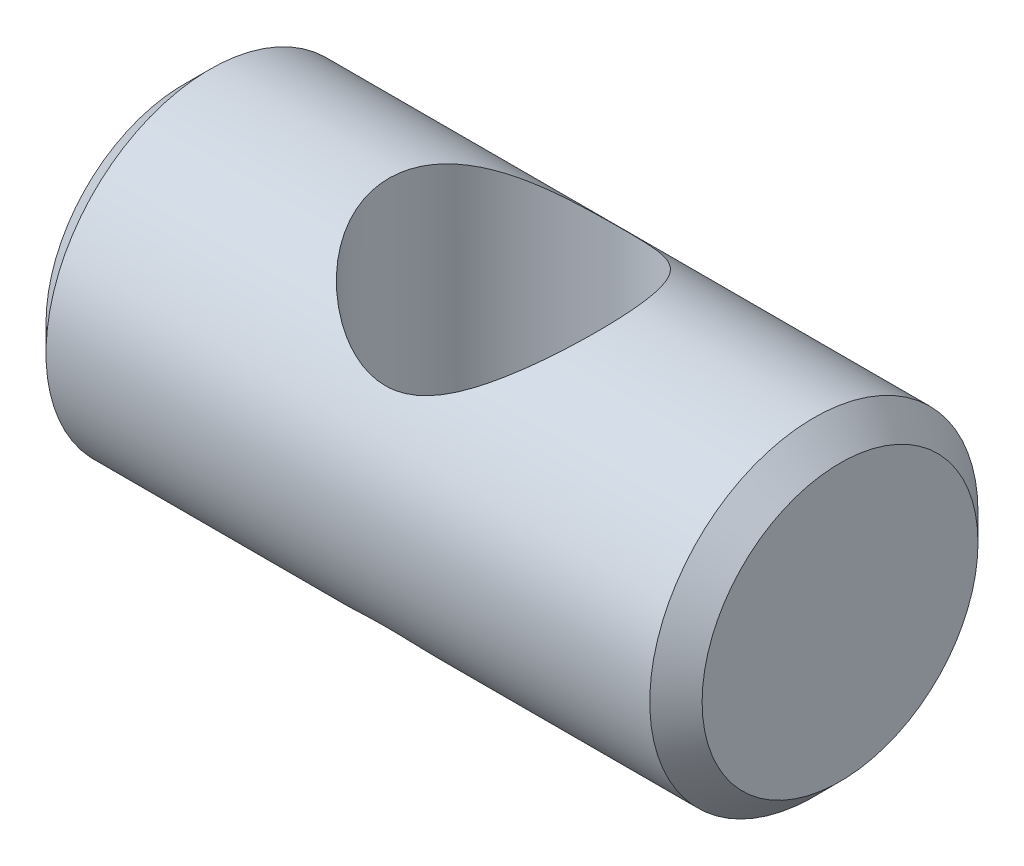
SolidWorks part; units mm, degrees
ref_plane "Front Plane" through (0, 0, 0) normal (0, 0, 1) x (1, 0, 0)
ref_plane "Top Plane" through (0, 0, 0) normal (0, 1, 0) x (1, 0, 0)
ref_plane "Right Plane" through (0, 0, 0) normal (1, 0, 0) x (0, 0, -1)
sketch "Sketch2" plane through (0, 0, 0) normal (1, 0, 0) x (0, 0, -1)
  circle A0 centre (0, 0) radius 4.765
extrude "Boss-Extrude1" add sketch "Sketch2" along normal mid plane 19.05
chamfer "Chamfer1" distance 0.76 angle 45 2 edges at (-9.525, 0, -4.765) (9.525, 0, -4.765)
sketch "Sketch3" plane through (0, 0, 0) normal (0, 1, 0) x (1, 0, 0)
  circle A0 centre (0, -0.25) radius 3.43
  dimension "D1" = 6.86
  dimension "D2" = 0.25
extrude "Cut-Extrude1" cut sketch "Sketch3" against normal mid plane 19.05
